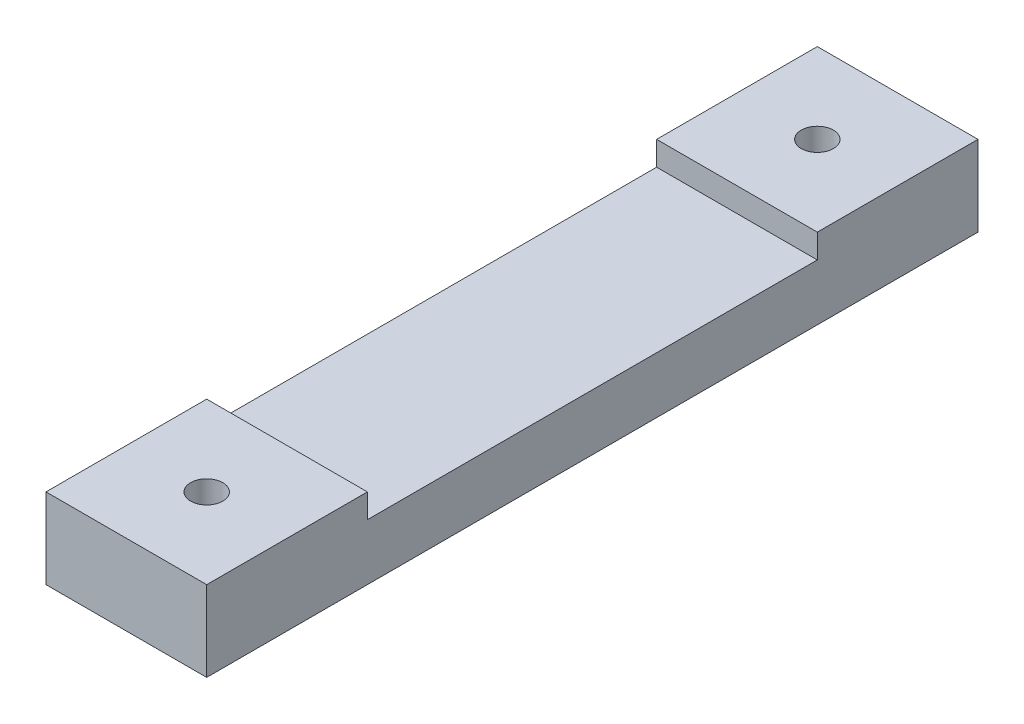
SolidWorks part; units mm, degrees
ref_plane "Front Plane" through (0, 0, 0) normal (0, 0, 1) x (1, 0, 0)
ref_plane "Top Plane" through (0, 0, 0) normal (0, 1, 0) x (1, 0, 0)
ref_plane "Right Plane" through (0, 0, 0) normal (1, 0, 0) x (0, 0, -1)
sketch "Sketch1" plane through (0, 0, 0) normal (0, 1, 0) x (1, 0, 0)
  line L0 (0.1456, 10.1033) -> (0.1456, -12.1175) construction
  line L1 (-4.8544, 22.9929) -> (5.1456, 22.9929)
  line L2 (-4.8544, 22.9929) -> (-4.8544, -25.0071)
  line L3 (-4.8544, -25.0071) -> (5.1456, -25.0071)
  line L4 (5.1456, 22.9929) -> (5.1456, -25.0071)
  line L5 (0.1456, -1.0071) -> (-13.7913, -1.0071) construction
  line L6 (13.7822, -1.0071) -> (13.8272, -1.0071) construction
  line L7 (13.8272, -1.0071) -> (0.1456, -1.0071) construction
  dimension "D1" = 10
  dimension "D2" = 48
  dimension "D3" = 5
  dimension "D4" = 24
extrude "Boss-Extrude1" add sketch "Sketch1" along normal blind 3.5
sketch "Sketch2" plane through (0, 3.5, 0) normal (0, 1, 0) x (1, 0, 0)
  line L0 (5.1456, -25.0071) -> (5.1456, 22.9929) construction
  line L1 (-4.8544, 22.9929) -> (5.1456, 22.9929)
  line L2 (-4.8544, 22.9929) -> (-4.8544, 12.9929)
  line L3 (-4.8544, 12.9929) -> (5.1456, 12.9929)
  line L4 (5.1456, 22.9929) -> (5.1456, 12.9929)
  line L6 (-4.8544, -25.0071) -> (5.1456, -25.0071)
  line L7 (-4.8544, -25.0071) -> (-4.8544, -15.0071)
  line L8 (-4.8544, -15.0071) -> (5.1456, -15.0071)
  line L9 (5.1456, -25.0071) -> (5.1456, -15.0071)
  dimension "D1" = 10
  dimension "D2" = 10
extrude "Boss-Extrude2" add sketch "Sketch2" along normal blind 1.5
sketch "Sketch3" plane through (0, 5, 0) normal (0, 1, 0) x (1, 0, 0)
  line L2 (-4.8544, 12.9929) -> (5.1456, 12.9929) construction
  line L3 (-4.8544, 22.9929) -> (-4.8544, 12.9929) construction
  line L5 (-4.8544, -15.0071) -> (-4.8544, -25.0071) construction
  line L6 (-4.8544, -25.0071) -> (5.1456, -25.0071) construction
  circle A0 centre (0.1456, 17.9929) radius 1
  circle A1 centre (0.1456, -20.0071) radius 1
  point P8 (30.8509, 13.5295)
  dimension "D1" = 5
  dimension "D2" = 5
  dimension "D3" = 5
  dimension "D4" = 5
extrude "Cut-Extrude1" cut sketch "Sketch3" against normal blind 5
